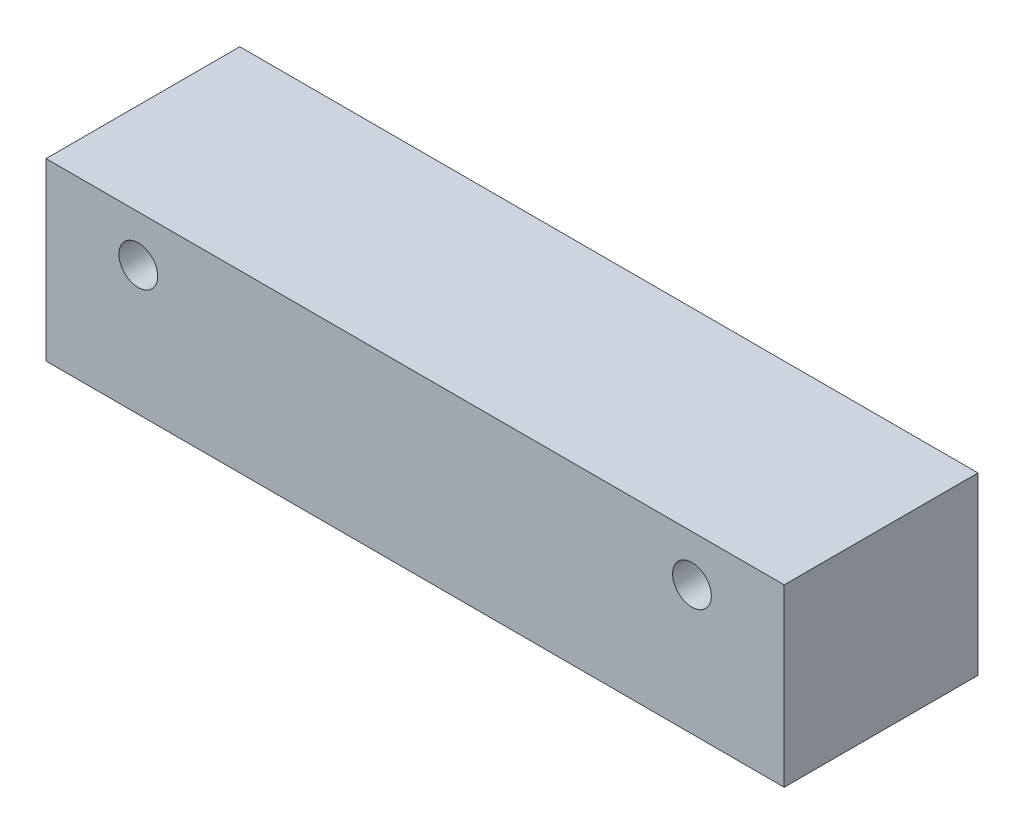
SolidWorks part; units mm, degrees
ref_plane "Front Plane" through (0, 0, 0) normal (0, 0, 1) x (1, 0, 0)
ref_plane "Top Plane" through (0, 0, 0) normal (0, 1, 0) x (1, 0, 0)
ref_plane "Right Plane" through (0, 0, 0) normal (1, 0, 0) x (0, 0, -1)
sketch "Sketch1" plane through (0, 0, 0) normal (0, 0, 1) x (1, 0, 0)
  line L1 (0, 0) -> (80, 0)
  line L2 (0, 0) -> (0, 19)
  line L3 (0, 19) -> (80, 19)
  line L4 (80, 0) -> (80, 19)
  dimension "D1" = 19
  dimension "D2" = 80
extrude "Boss-Extrude1" add sketch "Sketch1" along normal mid plane 21
hole_wizard "M5x0.8 Tapped Hole1" positions "Sketch2" profile "Sketch3" tap size "M5x0.8" standard "ANSI Metric" end condition through all
sketch "Sketch2" plane through (0, 0, 10.5) normal (0, 0, 1) x (1, 0, 0)
  line L0 (80, 19) -> (0, 19) construction
  line L1 (40, 19) -> (40, 0) construction
  line L2 (0, 0) -> (80, 0) construction
  circle A0 centre (10, 14) radius 4 construction
  point P0 (10, 14)
  point P5 (40, 19)
  point P12 (70, 14)
  dimension "D2" = 8
  dimension "D1" = 30
  dimension "D3" = 5
sketch "Sketch3" plane through (10, 14, 10.5) normal (1, 0, 0) x (0, -1, 0)
  line L0 (0, 0) -> (0, 21)
  line L1 (0, 21) -> (2.1, 21)
  line L2 (2.1, 21) -> (2.1, 0)
  line L5 (2.1, 0) -> (0, 0)
  line L11 (0, -6.35) -> (0, 107.95) construction
  dimension "Thru Tap Drill Dia." = 4.2
  dimension "Thru Tap Drill Depth" = 21
cosmetic thread "Hole Thread1" parameters "D2"=5
cosmetic thread "Hole Thread2" parameters "D2"=5
